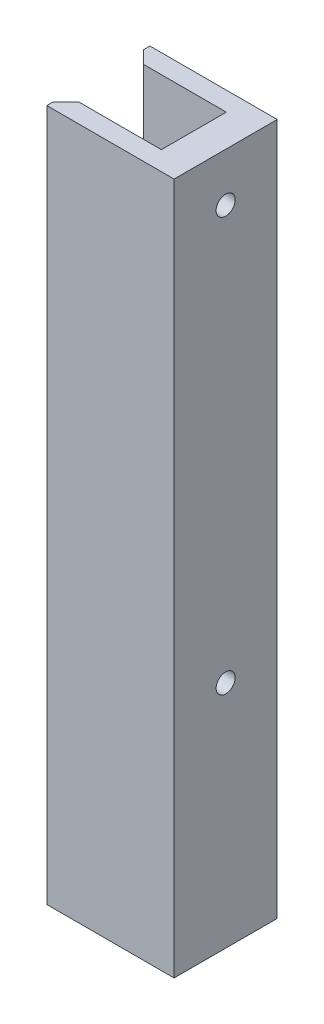
SolidWorks part; units mm, degrees
ref_plane "正面" through (0, 0, 0) normal (0, 0, 1) x (1, 0, 0)
ref_plane "平面" through (0, 0, 0) normal (0, 1, 0) x (1, 0, 0)
ref_plane "右側面" through (0, 0, 0) normal (1, 0, 0) x (0, 0, -1)
sketch "ｽｹｯﾁ1" plane through (-2.0348, 0, 0) normal (1, 0, 0) x (0, 0, -1)
  line L0 (-136, 45.4267) -> (-126, 45.4267)
  line L1 (-136.1, 45.5267) -> (-125.9, 45.5267)
  line L2 (-125.9, -60.1733) -> (-125.9, 45.5267)
  line L3 (-136.1, -60.1733) -> (-125.9, -60.1733)
  line L4 (-136, -60.0733) -> (-126, -60.0733)
  line L5 (-126, -60.0733) -> (-126, 70.9267)
  line L6 (-126, 70.9267) -> (-136, 70.9267)
  line L7 (-136, 70.9267) -> (-136, -60.0733)
  line L8 (-136, -60.0733) -> (-126, -60.0733)
  line L9 (-126, -60.0733) -> (-126, 45.4267)
  line L11 (-136, 45.4267) -> (-136, -60.0733)
  line L12 (-136.1, 45.5267) -> (-136.1, -60.1733)
  circle A0 centre (-131, 37.9267) radius 1.5
  circle A1 centre (-131, 37.9267) radius 1.6
  circle A2 centre (-131, 37.9267) radius 1.6 construction
  circle A3 centre (-131, -27.0733) radius 1.6
  circle A4 centre (-131, -27.0733) radius 1.6 construction
  circle A5 centre (-131, -27.0733) radius 1.5
  circle M8 centre (-131, -27.0733) radius 1.6
  circle M9 centre (-131, 37.9267) radius 1.6
  line M10 (-136, -60.0733) -> (-126, -60.0733)
  line M11 (-126, -60.0733) -> (-126, 70.9267)
  line M13 (-136, 70.9267) -> (-136, -60.0733)
  dimension "D4" = 7.5
  dimension "D1" = 0
  dimension "D2" = 0
  dimension "D3" = 0
  dimension "D5" = 0.1
  dimension "D6" = 0.1
extrude "ﾎﾞｽ - 押し出し1" add sketch "ｽｹｯﾁ1" along normal blind 5 contours L0 M13 M10 M11 M9 M8 | L1 L12 L3 L2 M11 M10 M13 | L1 L0 M13 M11 | A0 M9 | A5 M8
sketch "ｽｹｯﾁ2" plane through (0, -60.1733, 0) normal (0, -1, 0) x (1, 0, 0)
  line L0 (2.9652, 136.1) -> (2.9652, 125.9) construction
  line L1 (-17.0348, 139.1) -> (2.9652, 139.1)
  line L2 (-17.0348, 139.1) -> (-17.0348, 122.9)
  line L3 (-17.0348, 122.9) -> (2.9652, 122.9)
  line L4 (-2.0348, 126) -> (-2.0348, 136)
  line L5 (-2.0348, 136) -> (-17.0348, 136)
  line L6 (-17.0348, 136) -> (-17.0348, 126)
  line L7 (-17.0348, 126) -> (-2.0348, 126)
  line L8 (-2.0348, 126) -> (-2.0348, 136)
  line L10 (-17.0348, 136) -> (-17.0348, 126)
  line L12 (2.9652, 139.1) -> (2.9652, 122.9)
  line L13 (2.9652, 136.1) -> (-2.0348, 136.1) construction
  line L14 (2.9652, 125.9) -> (-2.0348, 125.9) construction
  line L15 (2.9652, 136.1) -> (-17.0348, 136.1)
  line L16 (2.9652, 125.9) -> (-17.0348, 125.9)
  line M10 (-2.0348, 125.9) -> (2.9652, 125.9)
  line M12 (2.9652, 136.1) -> (-2.0348, 136.1)
  dimension "D2" = 3
  dimension "D3" = 3
  dimension "D1" = 0
extrude "ﾎﾞｽ - 押し出し2" add sketch "ｽｹｯﾁ2" against normal up to surface (105.7 mm away) contours L15 L12 L1 L2 M12 | L16 L2 L3 L12 M10 up to face at (0.4652, 45.5267, 131)
chamfer "面取り1" distance 2 angle 45 2 edges at (-17.0348, -7.3233, 125.9) (-17.0348, -7.3233, 136.1)
sketch "ｽｹｯﾁ3" plane through (0, -60.1733, 0) normal (0, -1, 0) x (1, 0, 0)
  line L1 (-17.0348, 139.1) -> (2.9652, 139.1)
  line L2 (-17.0348, 139.1) -> (-17.0348, 122.9)
  line L3 (-17.0348, 122.9) -> (2.9652, 122.9)
  line L4 (2.9652, 139.1) -> (2.9652, 122.9)
  line L10 (-2.0348, 125.9) -> (-15.0348, 125.9)
  line L11 (-15.0348, 125.9) -> (-17.0348, 123.9)
  line L12 (-17.0348, 123.9) -> (-17.0348, 122.9)
  line L13 (-17.0348, 122.9) -> (2.9652, 122.9)
  line L14 (2.9652, 122.9) -> (2.9652, 139.1)
  line L15 (2.9652, 139.1) -> (-17.0348, 139.1)
  line L16 (-17.0348, 139.1) -> (-17.0348, 138.1)
  line L17 (-17.0348, 138.1) -> (-15.0348, 136.1)
  line L18 (-15.0348, 136.1) -> (-2.0348, 136.1)
  line L19 (-2.0348, 136.1) -> (-2.0348, 125.9)
  line L20 (-2.0348, 125.9) -> (-15.0348, 125.9)
  line L21 (-15.0348, 125.9) -> (-17.0348, 123.9)
  line L22 (-17.0348, 123.9) -> (-17.0348, 122.9)
  line L23 (-17.0348, 122.9) -> (2.9652, 122.9)
  line L24 (2.9652, 122.9) -> (2.9652, 139.1)
  line L25 (2.9652, 139.1) -> (-17.0348, 139.1)
  line L26 (-17.0348, 139.1) -> (-17.0348, 138.1)
  line L27 (-17.0348, 138.1) -> (-15.0348, 136.1)
  line L28 (-15.0348, 136.1) -> (-2.0348, 136.1)
  line L29 (-2.0348, 136.1) -> (-2.0348, 125.9)
  line M11 (-2.0348, 125.9) -> (-15.0348, 125.9)
  line M12 (-15.0348, 125.9) -> (-17.0348, 123.9)
  line M13 (-17.0348, 123.9) -> (-17.0348, 122.9)
  line M14 (-17.0348, 122.9) -> (2.9652, 122.9)
  line M15 (2.9652, 122.9) -> (2.9652, 139.1)
  line M16 (2.9652, 139.1) -> (-17.0348, 139.1)
  line M17 (-17.0348, 139.1) -> (-17.0348, 138.1)
  line M18 (-17.0348, 138.1) -> (-15.0348, 136.1)
  line M19 (-15.0348, 136.1) -> (-2.0348, 136.1)
  line M20 (-2.0348, 136.1) -> (-2.0348, 125.9)
  dimension "D1" = 0
extrude "ﾎﾞｽ - 押し出し3" add sketch "ｽｹｯﾁ3" along normal blind 3 contours M20 M11 M12 M13 M14 M15 M16 M17 M18 M19 | L2 M18 M12 M11 M20 M19
